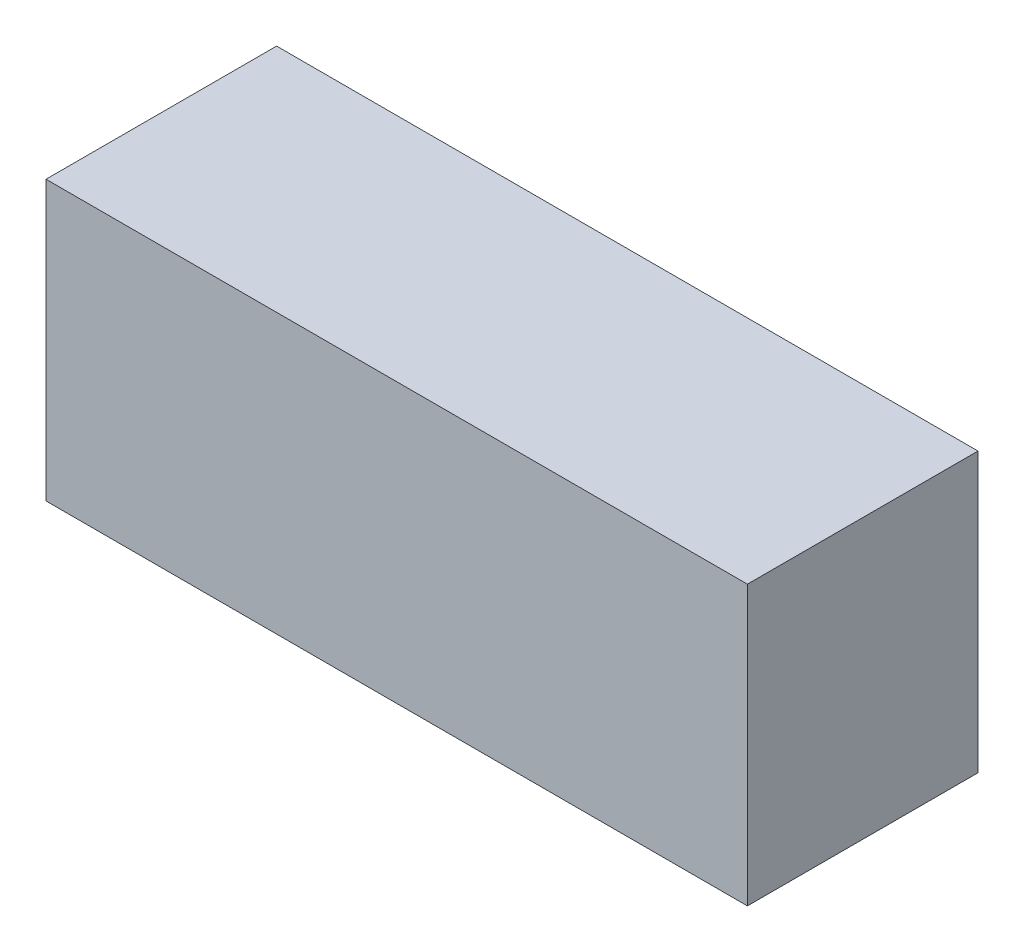
SolidWorks part; units mm, degrees
ref_plane "Front Plane" through (0, 0, 0) normal (0, 0, 1) x (1, 0, 0)
ref_plane "Top Plane" through (0, 0, 0) normal (0, 1, 0) x (1, 0, 0)
ref_plane "Right Plane" through (0, 0, 0) normal (1, 0, 0) x (0, 0, -1)
sketch "Sketch1" plane through (0, 0, 0) normal (0, 1, 0) x (1, 0, 0)
  line L1 (-3.65, -1.2) -> (3.65, -1.2)
  line L2 (-3.65, -1.2) -> (-3.65, 1.2)
  line L3 (-3.65, 1.2) -> (3.65, 1.2)
  line L4 (3.65, -1.2) -> (3.65, 1.2)
  line L5 (-3.65, -1.2) -> (3.65, 1.2) construction
  line L6 (-3.65, 1.2) -> (3.65, -1.2) construction
  point P0 (0, 0)
  dimension "D1" = 7.3
  dimension "D2" = 2.4
extrude "Boss-Extrude1" add sketch "Sketch1" along normal blind 2.9
